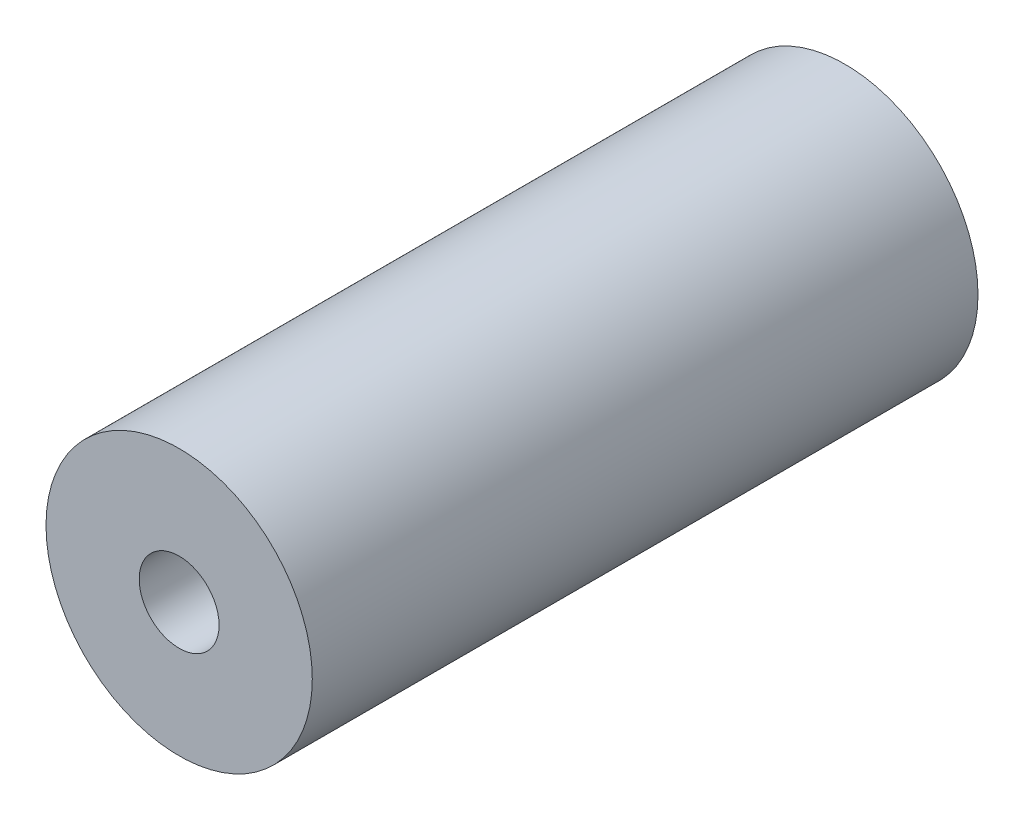
SolidWorks part; units mm, degrees
material "BUTİL"
ref_plane "Ön Düzlem" through (0, 0, 0) normal (0, 0, 1) x (1, 0, 0)
ref_plane "Üst Düzlem" through (0, 0, 0) normal (0, 1, 0) x (1, 0, 0)
ref_plane "Sağ Düzlem" through (0, 0, 0) normal (1, 0, 0) x (0, 0, -1)
sketch "Çizim1" plane through (0, 0, 0) normal (0, 0, 1) x (1, 0, 0)
  circle A0 centre (0, 0) radius 10
  dimension "D1" = 20
extrude "Yükseklik-Ekstrüzyon1" add sketch "Çizim1" along normal blind 50
sketch "Çizim2" plane through (0, 0, 50) normal (0, 0, 1) x (1, 0, 0)
  circle A0 centre (0, 0) radius 3
  dimension "D1" = 6
extrude "Kes-Ekstrüzyon1" cut sketch "Çizim2" against normal blind 45
